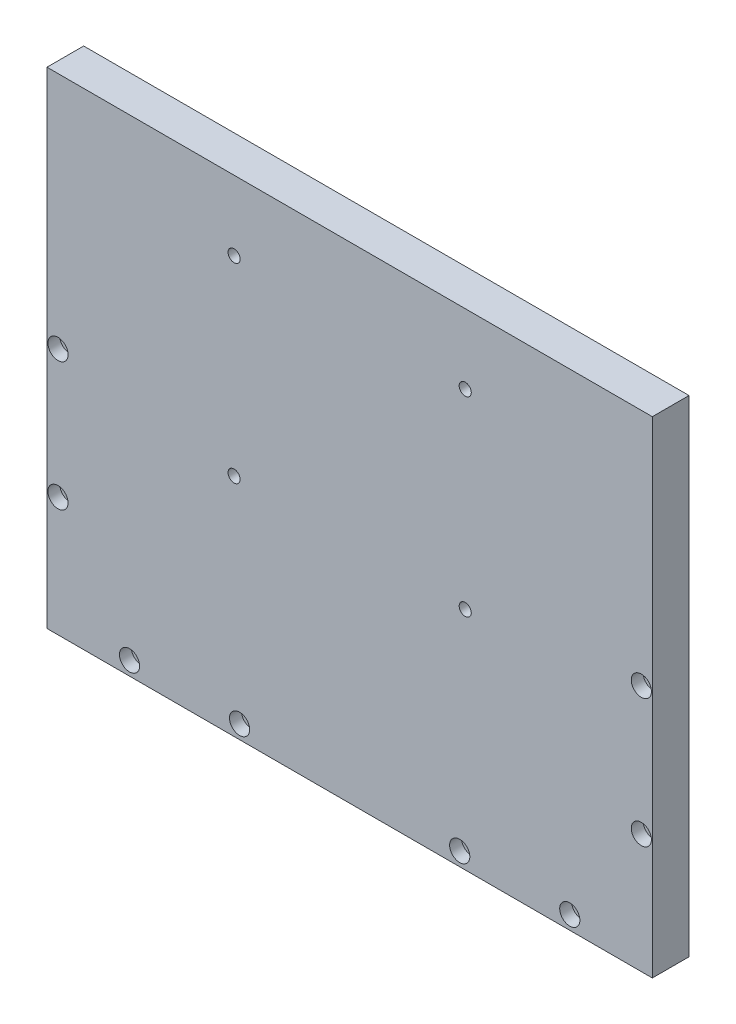
SolidWorks part; units mm, degrees
material "6061 合金"
ref_plane "前视基准面" through (0, 0, 0) normal (0, 0, 1) x (1, 0, 0)
ref_plane "上视基准面" through (0, 0, 0) normal (0, 1, 0) x (1, 0, 0)
ref_plane "右视基准面" through (0, 0, 0) normal (1, 0, 0) x (0, 0, -1)
other "Configuration Table"
sketch "Sketch1" plane through (0, 0, 0) normal (0, 0, 1) x (1, 0, 0)
  line L1 (-165, -175) -> (165, -175)
  line L2 (-165, -175) -> (-165, 90)
  line L3 (-165, 90) -> (165, 90)
  line L4 (165, -175) -> (165, 90)
extrude "Boss-Extrude1" add sketch "Sketch1" along normal blind 20
sketch "Sketch2" plane through (0, 0, 0) normal (0, 0, 1) x (1, 0, 0)
  circle A0 centre (-63, -52) radius 3.3
  circle A1 centre (-63, 52) radius 3.3
  circle A2 centre (63, -52) radius 3.3
  circle A3 centre (63, 52) radius 3.3
extrude "Cut-Extrude1" cut sketch "Sketch2" against normal through all and the other way through all
sketch "Sketch3" plane through (0, 0, 0) normal (0, 0, 1) x (1, 0, 0)
  circle A0 centre (-63, -52) radius 5.5
  circle A1 centre (-63, 52) radius 5.5
  circle A2 centre (63, -52) radius 5.5
  circle A3 centre (63, 52) radius 5.5
extrude "Cut-Extrude3" cut sketch "Sketch3" along normal blind 6.5
sketch "Sketch4" plane through (0, 0, 0) normal (0, 0, 1) x (1, 0, 0)
  circle A0 centre (-120, -167.5) radius 3.3
  circle A1 centre (-60, -167.5) radius 3.3
  circle A2 centre (60, -167.5) radius 3.3
  circle A3 centre (120, -167.5) radius 3.3
extrude "Cut-Extrude4" cut sketch "Sketch4" against normal through all and the other way through all
ref_plane "Plane1" through (0, 0, 20) normal (0, 0, 1) x (1, 0, 0)
sketch "Sketch5" plane through (0, 0, 20) normal (0, 0, 1) x (1, 0, 0)
  circle A0 centre (-120, -167.5) radius 5.5
  circle A1 centre (-60, -167.5) radius 5.5
  circle A2 centre (60, -167.5) radius 5.5
  circle A3 centre (120, -167.5) radius 5.5
extrude "Cut-Extrude6" cut sketch "Sketch5" against normal blind 6.5
sketch "Sketch6" plane through (0, 0, 0) normal (0, 0, 1) x (1, 0, 0)
  circle A0 centre (-159, -110) radius 3.3
  circle A1 centre (-159, -40) radius 3.3
  circle A2 centre (159, -110) radius 3.3
  circle A3 centre (159, -40) radius 3.3
extrude "Cut-Extrude7" cut sketch "Sketch6" against normal through all and the other way through all
ref_plane "Plane2" through (0, 0, 20) normal (0, 0, 1) x (1, 0, 0)
sketch "Sketch7" plane through (0, 0, 20) normal (0, 0, 1) x (1, 0, 0)
  circle A0 centre (-159, -110) radius 5.5
  circle A1 centre (-159, -40) radius 5.5
  circle A2 centre (159, -110) radius 5.5
  circle A3 centre (159, -40) radius 5.5
extrude "Cut-Extrude9" cut sketch "Sketch7" against normal blind 6.5
